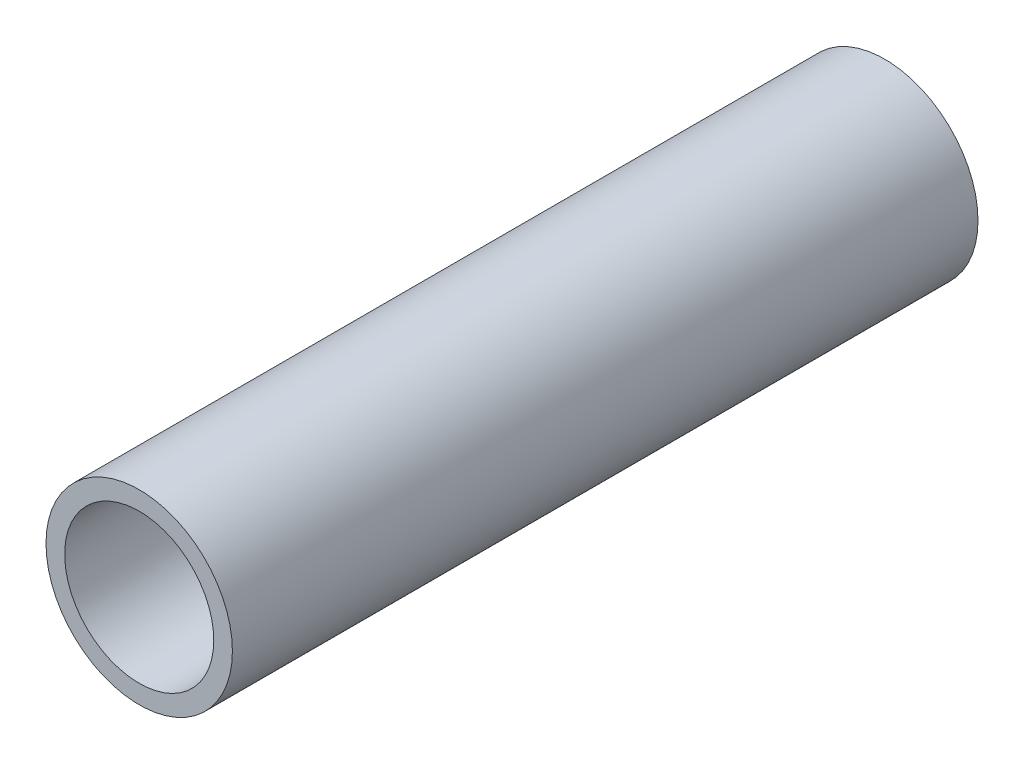
SolidWorks part; units mm, degrees
ref_plane "Front Plane" through (0, 0, 0) normal (0, 0, 1) x (1, 0, 0)
ref_plane "Top Plane" through (0, 0, 0) normal (0, 1, 0) x (1, 0, 0)
ref_plane "Right Plane" through (0, 0, 0) normal (1, 0, 0) x (0, 0, -1)
sketch "Sketch2" plane through (0, 0, 0) normal (0, 0, 1) x (1, 0, 0)
  circle A0 centre (0, 0) radius 50.8
  circle A1 centre (0, 0) radius 63.5
  dimension "D1" = 101.6
  dimension "D2" = 127
extrude "Boss-Extrude1" add sketch "Sketch2" along normal blind 508
